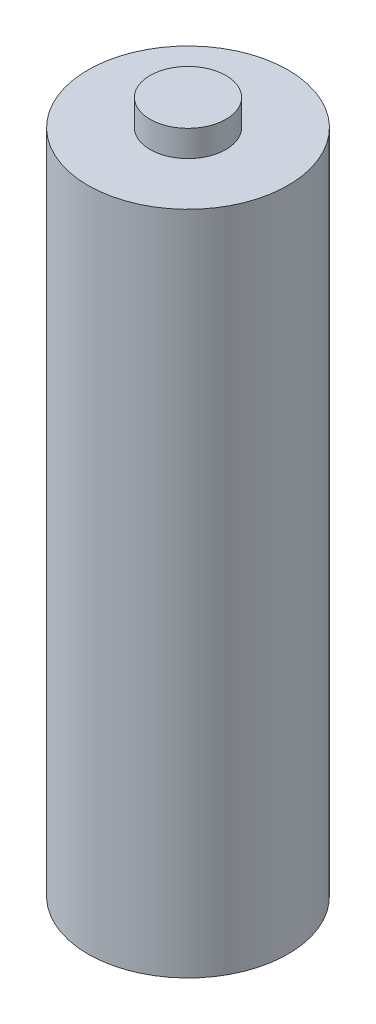
SolidWorks part; units mm, degrees
ref_plane "Front Plane" through (0, 0, 0) normal (0, 0, 1) x (1, 0, 0)
ref_plane "Top Plane" through (0, 0, 0) normal (0, 1, 0) x (1, 0, 0)
ref_plane "Right Plane" through (0, 0, 0) normal (1, 0, 0) x (0, 0, -1)
sketch "Sketch1" plane through (0, 0, 0) normal (0, 0, 1) x (1, 0, 0)
  line L0 (0, 0) -> (0, 52.8036) construction
  line L1 (0, 50.4) -> (2.75, 50.4)
  line L2 (2.75, 50.4) -> (2.75, 48.5)
  line L3 (2.75, 48.5) -> (7.25, 48.5)
  line L4 (7.25, 48.5) -> (7.25, 0.25)
  line L5 (7.25, 0.25) -> (4.7, 0.25)
  line L6 (4.7, 0.25) -> (4.7, 0)
  line L7 (4.7, 0) -> (0, 0)
  line L8 (0, 0) -> (0, 50.4)
  dimension "D1" = 14.5
  dimension "D2" = 50.4
  dimension "D3" = 9.4
  dimension "D4" = 5.5
  dimension "D5" = 1.9
  dimension "D6" = 0.25
revolve "Revolve1" add sketch "Sketch1" angle 360 about L0
